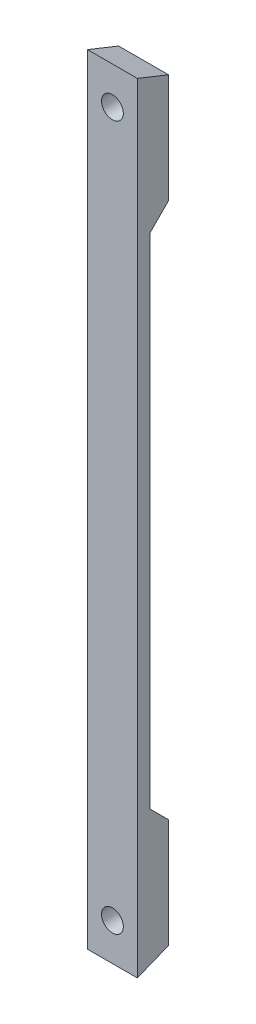
SolidWorks part; units mm, degrees
ref_plane "Front Plane" through (0, 0, 0) normal (1, 0, 0) x (0, 1, 0)
ref_plane "Top Plane" through (0, 0, 0) normal (0, 0, 1) x (0, 1, 0)
ref_plane "Right Plane" through (0, 0, 0) normal (0, 1, 0) x (-1, 0, 0)
sketch "Sketch1" plane through (0, 0, 0) normal (0, 0, 1) x (0, 1, 0)
  line L1 (62.5, -4) -> (-62.5, -4)
  line L2 (62.5, -4) -> (62.5, 4)
  line L3 (62.5, 4) -> (-62.5, 4)
  line L4 (-62.5, -4) -> (-62.5, 4)
  line L5 (62.5, -4) -> (-62.5, 4) construction
  line L6 (62.5, 4) -> (-62.5, -4) construction
  circle A2 centre (-56.5, 0) radius 1.75
  circle A3 centre (56.5, 0) radius 1.75
  point P0 (0, 0)
  point P5 (-56.5, 0)
  point P6 (56.5, 0)
  point P12 (0, 0)
  point P13 (0, 0)
  dimension "D3" = 56.5
  dimension "D5" = 3.5
  dimension "D1" = 8
  dimension "D2" = 125
  dimension "D4" = 56.5
extrude "Boss-Extrude1" add sketch "Sketch1" along normal blind 5
sketch "Sketch2" plane through (4, 0, 0) normal (1, 0, 0) x (0, 1, 0)
  line L0 (-62.5, 5) -> (-60.5, 0)
  line L1 (-62.5, 0) -> (62.5, 0) construction
  line L2 (-43, 0) -> (-40, 3)
  line L3 (-40, 3) -> (40, 3)
  line L4 (40, 3) -> (43, 0)
  line L5 (60.5, 0) -> (62.5, 5)
  line L6 (62.5, 5) -> (62.5, 0) construction
  line L7 (-62.5, 5) -> (-62.5, 0) construction
  point P12 (0, 0)
  point P18 (42.9167, 0)
  line M2 (-62.5, 0) -> (62.5, 0)
  line M3 (62.5, 0) -> (62.5, 5)
  line M5 (-62.5, 5) -> (-62.5, 0)
  dimension "D1" = 2
  dimension "D2" = 2
  dimension "D3" = 3
  dimension "D4" = 40
  dimension "D5" = 40
  dimension "D6" = 3
  dimension "D7" = 3
extrude "Cut-Extrude1" cut sketch "Sketch2" against normal through all contours L4 L3 L2 M2 | L0 M5 M2 | L5 M2 M3
chamfer "Chamfer1" distance 2 angle 45 2 edges at (1.75, 56.5, 0) (1.75, -56.5, 0)
